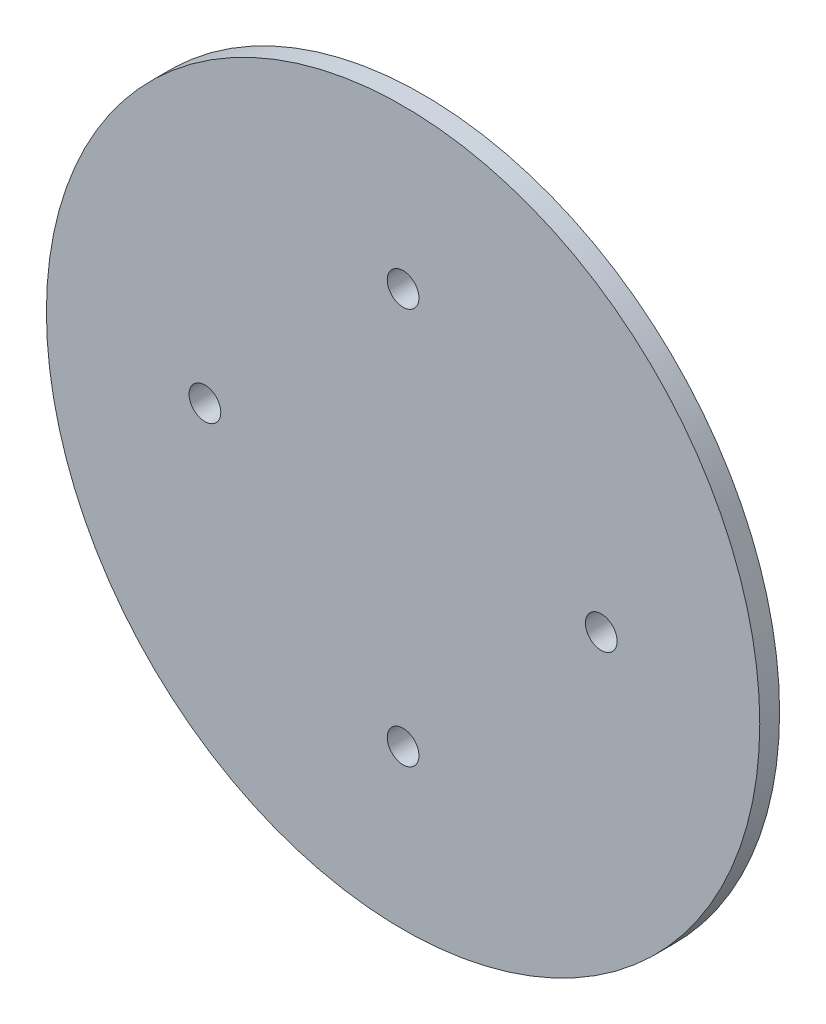
SolidWorks part; units mm, degrees
material "ABS"
ref_plane "正面" through (0, 0, 0) normal (0, 0, 1) x (1, 0, 0)
ref_plane "平面" through (0, 0, 0) normal (0, 1, 0) x (1, 0, 0)
ref_plane "右側面" through (0, 0, 0) normal (1, 0, 0) x (0, 0, -1)
sketch "ｽｹｯﾁ1" plane through (0, 0, 0) normal (0, 0, 1) x (1, 0, 0)
  circle A0 centre (0, 0) radius 23.5
  dimension "D1" = 47
extrude "ﾎﾞｽ - 押し出し1" add sketch "ｽｹｯﾁ1" along normal blind 4
sketch "ｽｹｯﾁ2" plane through (0, 0, 0) normal (0, 0, -1) x (-1, 0, 0)
  circle A0 centre (0, 0) radius 22.225
  dimension "D1" = 44.45
extrude "ﾎﾞｽ - 押し出し2" add sketch "ｽｹｯﾁ2" along normal blind 3.175
sketch "ｽｹｯﾁ3" plane through (0, 0, -3.175) normal (0, 0, -1) x (-1, 0, 0)
  circle A0 centre (0, 0) radius 20 construction
  circle A1 centre (0, 20) radius 1.6
  circle A2 centre (20, 0) radius 1.6
  circle A3 centre (0, -20) radius 1.6
  circle A4 centre (-20, 0) radius 1.6
  point P14 (0, 0)
  dimension "D1" = 40
  dimension "D2" = 3.2
  dimension "D3" = 4
extrude "ｶｯﾄ - 押し出し1" cut sketch "ｽｹｯﾁ3" against normal through all
sketch "ｽｹｯﾁ4" plane through (0, 0, 4) normal (0, 0, 1) x (1, 0, 0)
  circle A0 centre (0, 0) radius 36
  circle A1 centre (0, 20) radius 1.6 construction
  circle A2 centre (-20, 0) radius 1.6 construction
  circle A3 centre (0, -20) radius 1.6 construction
  circle A4 centre (20, 0) radius 1.6 construction
  circle A5 centre (0, 20) radius 1.6
  circle A6 centre (-20, 0) radius 1.6
  circle A7 centre (0, -20) radius 1.6
  circle A8 centre (20, 0) radius 1.6
  dimension "D1" = 72
extrude "ﾎﾞｽ - 押し出し3" add sketch "ｽｹｯﾁ4" along normal blind 2
